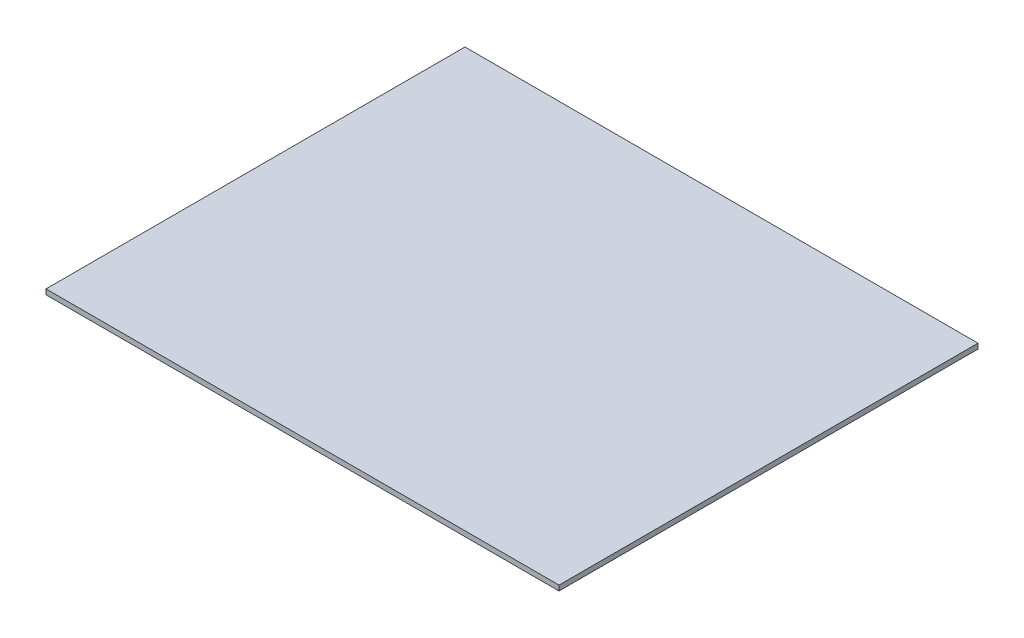
SolidWorks part; units mm, degrees
ref_plane "Front Plane" through (0, 0, 0) normal (0, 0, 1) x (1, 0, 0)
ref_plane "Top Plane" through (0, 0, 0) normal (0, 1, 0) x (1, 0, 0)
ref_plane "Right Plane" through (0, 0, 0) normal (1, 0, 0) x (0, 0, -1)
sketch "Sketch1" plane through (0, 0, 0) normal (0, 1, 0) x (1, 0, 0)
  line L1 (-245.6842, 79.8947) -> (54.3158, 79.8947)
  line L2 (-245.6842, 79.8947) -> (-245.6842, -165.1053)
  line L3 (-245.6842, -165.1053) -> (54.3158, -165.1053)
  line L4 (54.3158, 79.8947) -> (54.3158, -165.1053)
  dimension "D1" = 300
  dimension "D2" = 245
extrude "Boss-Extrude1" add sketch "Sketch1" along normal blind 3
